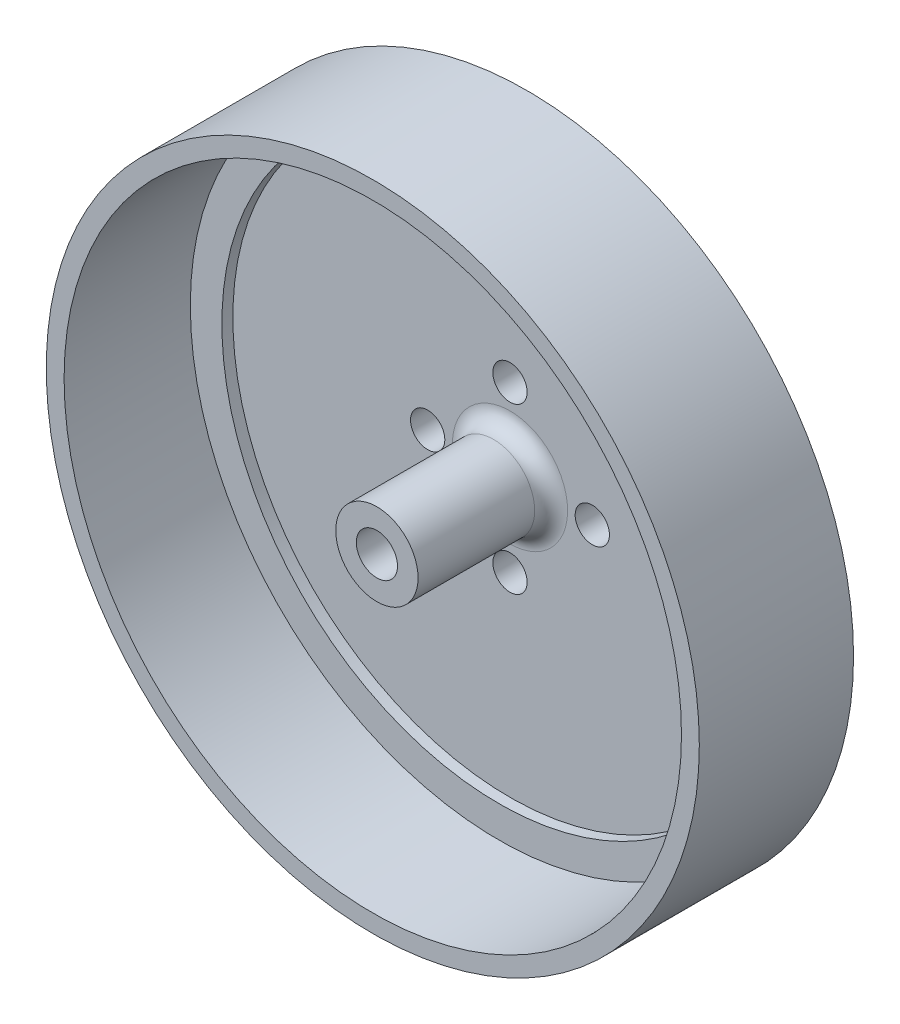
SolidWorks part; units mm, degrees
material "Plain Carbon Steel"
ref_plane "Front Plane" through (0, 0, 0) normal (0, 0, 1) x (1, 0, 0)
ref_plane "Top Plane" through (0, 0, 0) normal (0, 1, 0) x (1, 0, 0)
ref_plane "Right Plane" through (0, 0, 0) normal (1, 0, 0) x (0, 0, -1)
sketch "Sketch1" plane through (0, 0, 0) normal (0, 0, 1) x (1, 0, 0)
  circle A0 centre (0, 0) radius 23.8
  dimension "D2" = 47.6
extrude "Boss-Extrude1" add sketch "Sketch1" along normal blind 2.3
sketch "Sketch2" plane through (0, 0, 2.3) normal (0, 0, 1) x (1, 0, 0)
  circle A0 centre (0, 0) radius 23.8
  circle A1 centre (0, 0) radius 20.2
  dimension "D1" = 40.4
extrude "Boss-Extrude2" add sketch "Sketch2" along normal blind 10
sketch "Sketch3" plane through (0, 0, 2.3) normal (0, 0, 1) x (1, 0, 0)
  circle A0 centre (0, 0) radius 3
extrude "Boss-Extrude3" add sketch "Sketch3" along normal blind 9.7
chamfer "Chamfer1" distance 6 angle 10 1 edges at (23.8, 0, 0)
sketch "Sketch4" plane through (0, 0, 0) normal (0, 0, -1) x (-1, 0, 0)
  circle A0 centre (0, 0) radius 6 construction
  circle A1 centre (6, 0) radius 1.25
  circle A2 centre (0, -6) radius 1.25
  circle A3 centre (-6, 0) radius 1.25
  circle A4 centre (0, 6) radius 1.25
  point P14 (0, 0)
  dimension "D1" = 12
  dimension "D2" = 4
  dimension "D3" = 2.5
extrude "Cut-Extrude1" cut sketch "Sketch4" against normal blind 15
sketch "Sketch6" plane through (0, 0, 12.3) normal (0, 0, 1) x (1, 0, 0)
  circle A0 centre (0, 0) radius 22.5
  circle A1 centre (0, 0) radius 20.2
extrude "Cut-Extrude3" cut sketch "Sketch6" against normal blind 9.2
sketch "Sketch7" plane through (0, 0, 12) normal (0, 0, 1) x (1, 0, 0)
  circle A0 centre (0, 0) radius 1.5
  dimension "D1" = 3
extrude "Cut-Extrude4" cut sketch "Sketch7" against normal blind 5
fillet "Redondeo1" radius 1.2 1 edges at (3, 0, 2.3)
sketch "Croquis1" plane through (0, 0, 0) normal (0, 0, -1) x (-1, 0, 0)
  circle A0 centre (0, 0) radius 9.3393
  circle A1 centre (0, 6) radius 1.25
  circle A2 centre (6, 0) radius 1.25
  circle A3 centre (0, -6) radius 1.25
  circle A4 centre (-6, 0) radius 1.25
  circle A5 centre (-6, 0) radius 1.25 construction
extrude "Saliente-Extruir1" add sketch "Croquis1" along normal blind 1
sketch "Croquis2" plane through (0, 0, -1) normal (0, 0, -1) x (-1, 0, 0)
  circle A0 centre (0, 0) radius 2
  dimension "D1" = 4
extrude "Saliente-Extruir2" add sketch "Croquis2" along normal blind 3
